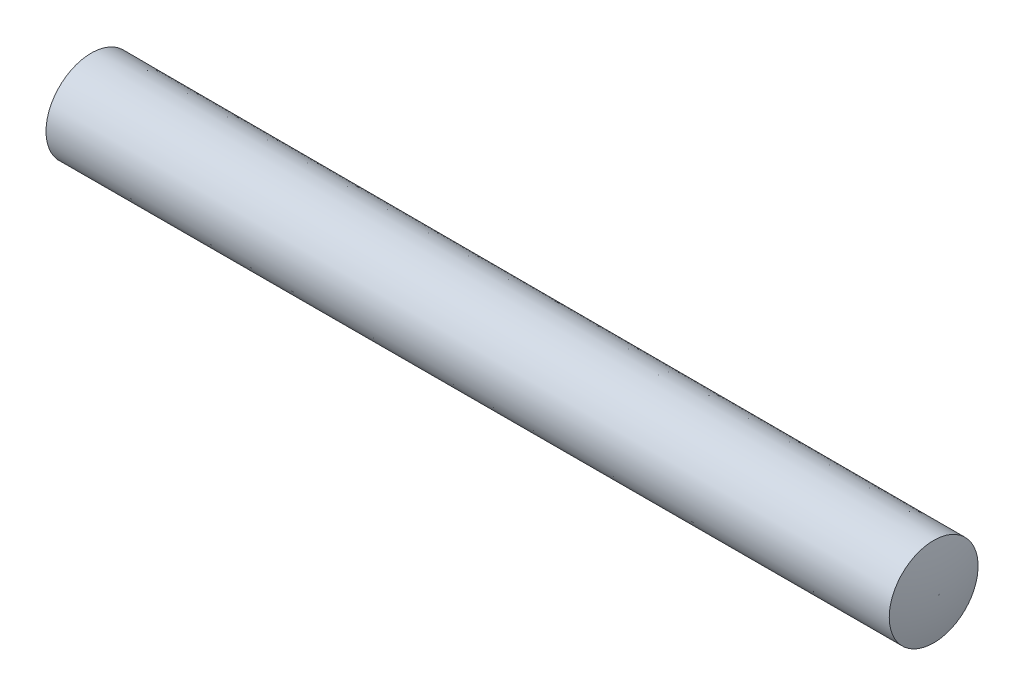
SolidWorks part; units mm, degrees
ref_plane "Plane1" through (0, 0, 0) normal (0, 0, 1) x (1, 0, 0)
ref_plane "Plane2" through (0, 0, 0) normal (0, 1, 0) x (1, 0, 0)
ref_plane "Plane3" through (0, 0, 0) normal (1, 0, 0) x (0, 0, -1)
sketch "Sketch1" plane through (0, 0, 0) normal (0, 0, 1) x (1, 0, 0)
  line L1 (-5.588, 0) -> (131.826, 0) construction
  line L2 (0, 0) -> (0, 0.0119)
  line L3 (0, 0) -> (22.5166, 0)
  line L4 (22.5166, 0) -> (22.5166, 0.0119)
  line L5 (22.3736, 1.172) -> (0.1486, 1.1938)
  arc A0 (0, 0.0119) -> (0.1486, 1.1938) centre (4.7752, 0.0119) cw
  arc A1 (22.5166, 0.0119) -> (22.3736, 1.172) centre (17.7414, 0.0119) ccw
  dimension "D3" = 4.7752
  dimension "D4" = 4.7752
  dimension "D1" = 0.0119
  dimension "D2" = 0.0119
  dimension "Length" = 22.225
  dimension "Diameter" = 2.3876
  dimension "D5" = 2.3441
revolve "Base-Revolve" add sketch "Sketch1" angle 360 about L1
equation "\"D1@Sketch1\" = \"Diameter@Sketch1\" / 100 / 2"
equation "\"D2@Sketch1\" = \"Diameter@Sketch1\" / 100 / 2"
equation "\"D3@Sketch1\" = \"Diameter@Sketch1\" *2"
equation "\"D4@Sketch1\" = \"Diameter@Sketch1\" *2"
equation "\"D5@Sketch1\" = \"Diameter@Sketch1\" -  (\"Length@Sketch1\" * (1/48) * \"Diameter@Sketch1\")"
